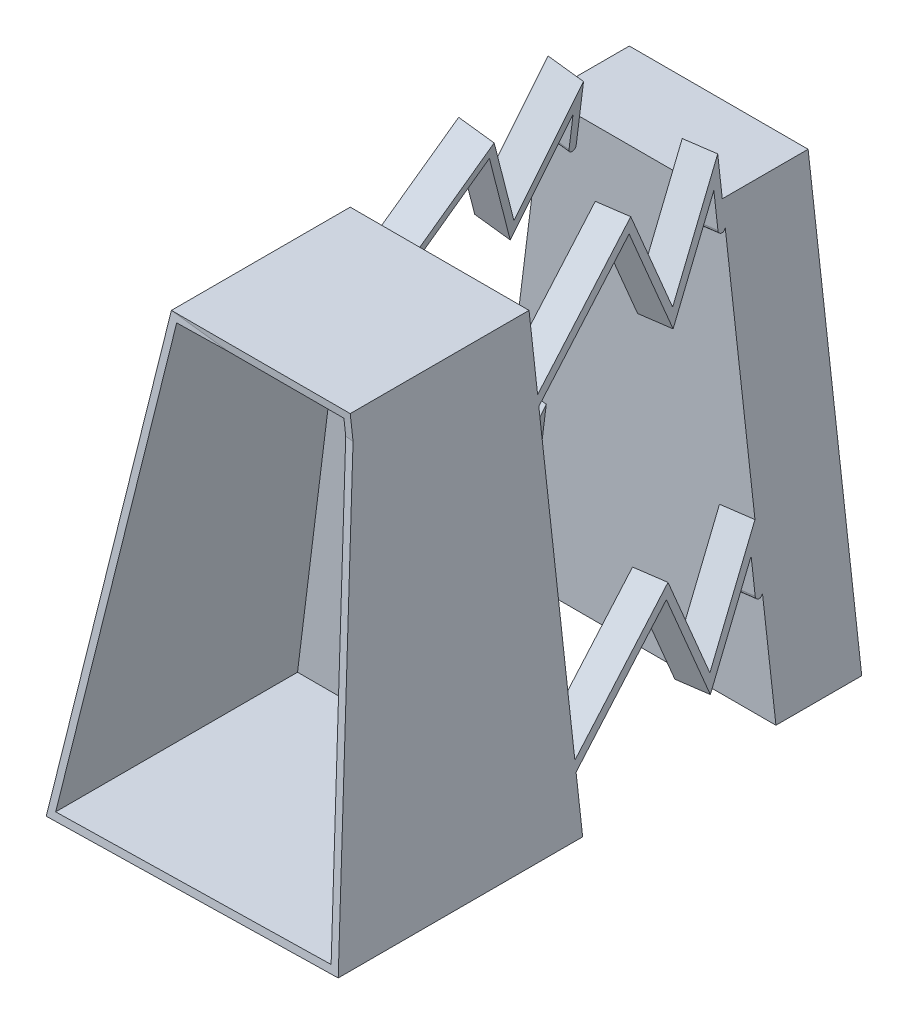
SolidWorks part; units mm, degrees
ref_plane "Front Plane" through (0, 0, 0) normal (0, 0, 1) x (1, 0, 0)
ref_plane "Top Plane" through (0, 0, 0) normal (0, 1, 0) x (1, 0, 0)
ref_plane "Right Plane" through (0, 0, 0) normal (1, 0, 0) x (0, 0, -1)
sketch "Sketch1" plane through (0, 0, 0) normal (0, 0, 1) x (1, 0, 0)
  line L0 (-125, 424.3355) -> (125, 424.3355)
  line L1 (-200, -175.6645) -> (200, -175.6645)
  line L2 (-125, 424.3355) -> (-200, -175.6645)
  line L3 (125, 424.3355) -> (200, -175.6645)
  point P4 (0, 424.3355)
  point P5 (0, -175.6645)
  dimension "D1" = 250
  dimension "D2" = 400
  dimension "D3" = 600
extrude "Boss-Extrude1" add sketch "Sketch1" along normal blind 350
shell "Shell1" thickness 10
sketch "Sketch2" plane through (-175.3028, 21.9129, 0) normal (-0.9923, 0.124, 0) x (0, 0, 1)
  line L1 (350, 405.5544) -> (0, 405.5544) construction
  line L2 (250, 405.5544) -> (350, -199.1149)
  line L3 (250, 405.5544) -> (350, 405.5544)
  line L4 (350, 405.5544) -> (350, -199.1149)
extrude "Cut-Extrude1" cut sketch "Sketch2" against normal blind 436
sketch "Sketch3" plane through (-175.3028, 21.9129, 0) normal (-0.9923, 0.124, 0) x (0, 0, 1)
  line L1 (250, 405.5544) -> (509.761, 405.5544)
  line L2 (250, 405.5544) -> (250, 501.9645)
  line L3 (250, 501.9645) -> (509.761, 501.9645)
  line L4 (509.761, 405.5544) -> (509.761, 501.9645)
extrude "Cut-Extrude2" cut sketch "Sketch3" against normal through all
sketch "Sketch5" plane through (-175.3028, 21.9129, 0) normal (-0.9923, 0.124, 0) x (0, 0, 1)
  line L0 (0, -124.7449) -> (-142.4672, 5.816)
  line L1 (0, 405.5544) -> (0, -199.1149) construction
  line L2 (-142.4672, 5.816) -> (-187.7516, -124.7449)
  line L3 (-187.7516, -124.7449) -> (-260.2066, 0)
  line L4 (-260.2066, 0) -> (-260.2066, -46.21)
  line L5 (0, 295.2551) -> (-142.4672, 425.816)
  line L6 (-142.4672, 425.816) -> (-187.7516, 295.2551)
  line L7 (-187.7516, 295.2551) -> (-260.2066, 420)
  line L8 (-260.2066, 420) -> (-260.2066, 373.79)
  line L9 (6.7563, 302.6275) -> (-146.9288, 443.4689)
  line L10 (-146.9288, 443.4689) -> (-190.0548, 319.1308)
  line L11 (-190.0548, 319.1308) -> (-270.2066, 457.1272)
  line L12 (-270.2066, 457.1272) -> (-270.2066, 373.79)
  line L13 (6.7563, -117.3725) -> (-146.9288, 23.4689)
  line L14 (-146.9288, 23.4689) -> (-190.0548, -100.8692)
  line L15 (-190.0548, -100.8692) -> (-270.2066, 37.1272)
  line L16 (-270.2066, 37.1272) -> (-270.2066, -46.21)
  arc A0 (0, 295.2551) -> (6.7563, 302.6275) centre (3.3781, 298.9413) ccw
  arc A1 (-260.2066, 373.79) -> (-270.2066, 373.79) centre (-265.2066, 373.79) cw
  arc A2 (0, -124.7449) -> (6.7563, -117.3725) centre (3.3781, -121.0587) ccw
  arc A3 (-260.2066, -46.21) -> (-270.2066, -46.21) centre (-265.2066, -46.21) cw
  dimension "D2" = 10
  dimension "D3" = 10
  dimension "D1" = 2
extrude "Boss-Extrude2" add sketch "Sketch5" against normal blind 50
mirror "Mirror1" about plane through (0, 0, 0) normal (1, 0, 0) of "Boss-Extrude2"
sketch "Sketch6" plane through (0, 0, -270.2066) normal (0, 0, -1) x (-1, 0, 0)
  line L0 (-200, -175.6645) -> (-125, 424.3355)
  line L3 (-200, -175.6645) -> (200, -175.6645)
  line L5 (-125, 424.3355) -> (125, 424.3355)
  line L6 (125, 424.3355) -> (200, -175.6645)
  point P4 (0, -175.6645)
extrude "Boss-Extrude3" add sketch "Sketch6" along normal blind 120
sketch "Sketch7" plane through (0, 0, -390.2066) normal (0, 0, -1) x (-1, 0, 0)
  line L0 (-192.9728, -170.053) -> (-114.8861, 414.2506)
  line L7 (190.2801, -170.053) -> (-192.9728, -170.053)
  line L9 (-114.8861, 414.2506) -> (113.9886, 414.2506)
  line L10 (113.9886, 414.2506) -> (190.2801, -170.053)
extrude "Cut-Extrude3" cut sketch "Sketch7" against normal blind 110
